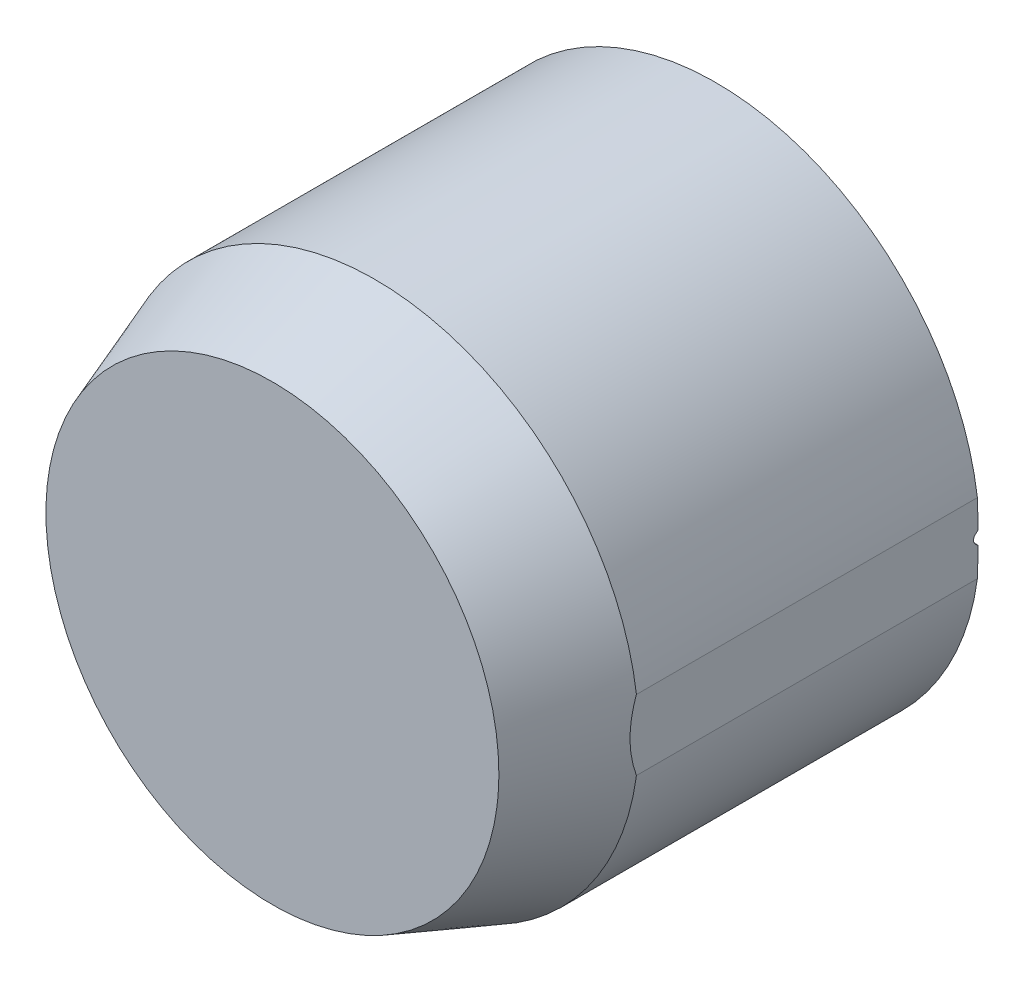
SolidWorks part; units mm, degrees
ref_plane "Front" through (0, 0, 0) normal (0, 0, 1) x (1, 0, 0)
ref_plane "Top" through (0, 0, 0) normal (0, 1, 0) x (1, 0, 0)
ref_plane "Right" through (0, 0, 0) normal (1, 0, 0) x (0, 0, -1)
sketch "Sketch1" plane through (0, 0, 0) normal (1, 0, 0) x (0, 0, -1)
  line L0 (0, 0) -> (15.6, 0)
  line L1 (0, 0) -> (0, 7.7261)
  line L2 (0, 7.7261) -> (3.5, 9)
  line L3 (3.5, 9) -> (15.1311, 9)
  line L4 (15.1311, 9) -> (15.6, 7.25)
  line L5 (15.6, 7.25) -> (15.6, 0)
  dimension "D1" = 15.6
  dimension "D2" = 9
  dimension "D3" = 15
  dimension "D4" = 20
  dimension "D5" = 3.5
  dimension "D6" = 7.25
revolve "Revolve1" add sketch "Sketch1" angle 360 about L0
sketch "Sketch2" plane through (0, 0, 0) normal (0, 0, 1) x (1, 0, 0)
  line L1 (8.92, 10.6684) -> (12.7953, 10.6684)
  line L2 (8.92, 10.6684) -> (8.92, -12.1217)
  line L3 (8.92, -12.1217) -> (12.7953, -12.1217)
  line L4 (12.7953, 10.6684) -> (12.7953, -12.1217)
  circle A0 centre (0, 0) radius 9 construction
  dimension "D1" = 17.92
extrude "Cut-Extrude1" cut sketch "Sketch2" against normal through all
sketch "Sketch3" plane through (0, 0, 0) normal (1, 0, 0) x (0, 0, -1)
  line L0 (15.0709, 0.1527) -> (15.6, 0.6)
  line L1 (15.6, -7.25) -> (15.6, 7.25) construction
  line L2 (15.0709, -0.1527) -> (15.6, -0.6)
  line L3 (15.6, 0.6) -> (15.6, -0.6)
  circle A0 centre (17.4, 0) radius 2.5 construction
  arc A1 (15.0709, -0.1527) -> (15.0709, 0.1527) centre (15.2, 0) cw
  point P11 (14.8902, 0)
  dimension "D1" = 5
  dimension "D3" = 0.2
  dimension "D5" = 0.6
  dimension "D2" = 14.9
  dimension "D4" = 1.2
extrude "Cut-Extrude2" cut sketch "Sketch3" against normal through all both and the other way through all
